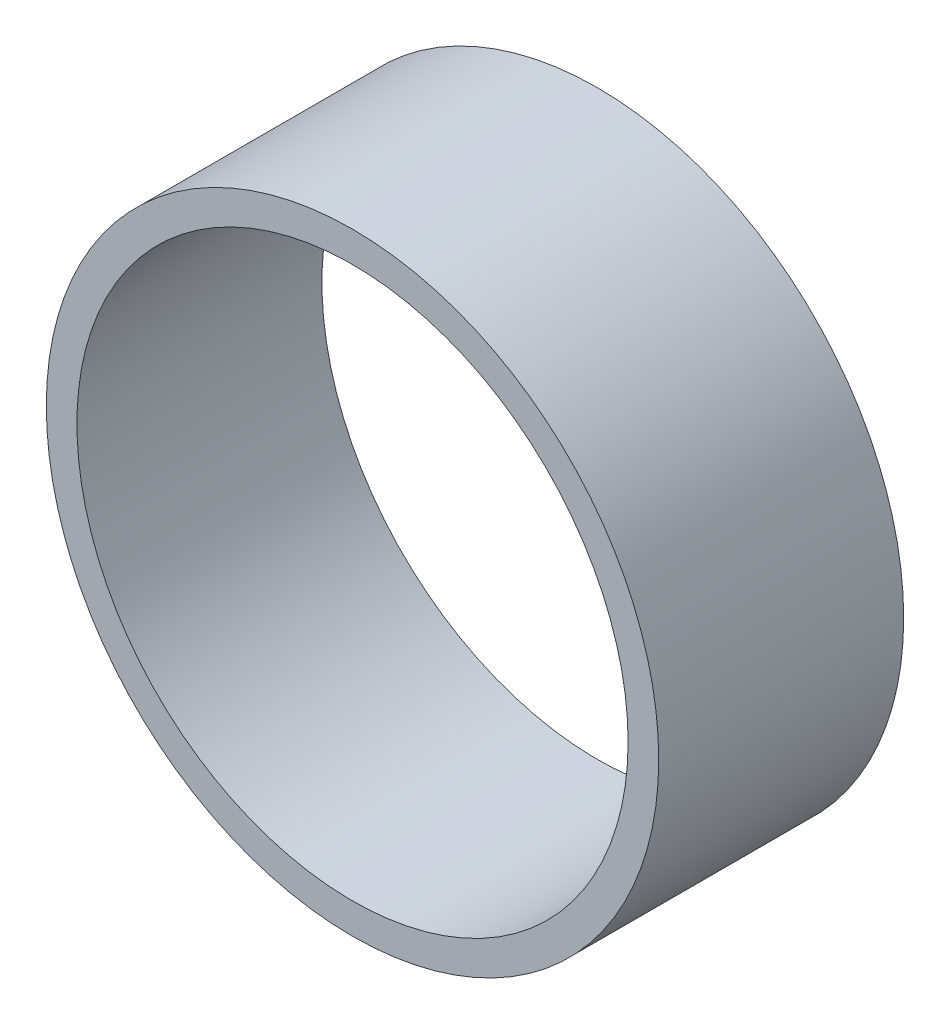
SolidWorks part; units mm, degrees
ref_plane "Plan de face" through (0, 0, 0) normal (0, 0, 1) x (1, 0, 0)
ref_plane "Plan de dessus" through (0, 0, 0) normal (0, 1, 0) x (1, 0, 0)
ref_plane "Plan de droite" through (0, 0, 0) normal (1, 0, 0) x (0, 0, -1)
sketch "Esquisse1" plane through (0, 0, 0) normal (0, 0, 1) x (1, 0, 0)
  circle A0 centre (0, 0) radius 10
  circle A1 centre (0, 0) radius 9
  dimension "D1" = 20
  dimension "D2" = 18
extrude "Boss.-Extru.1" add sketch "Esquisse1" along normal blind 8
equation "\"è.2\"=14.4"
